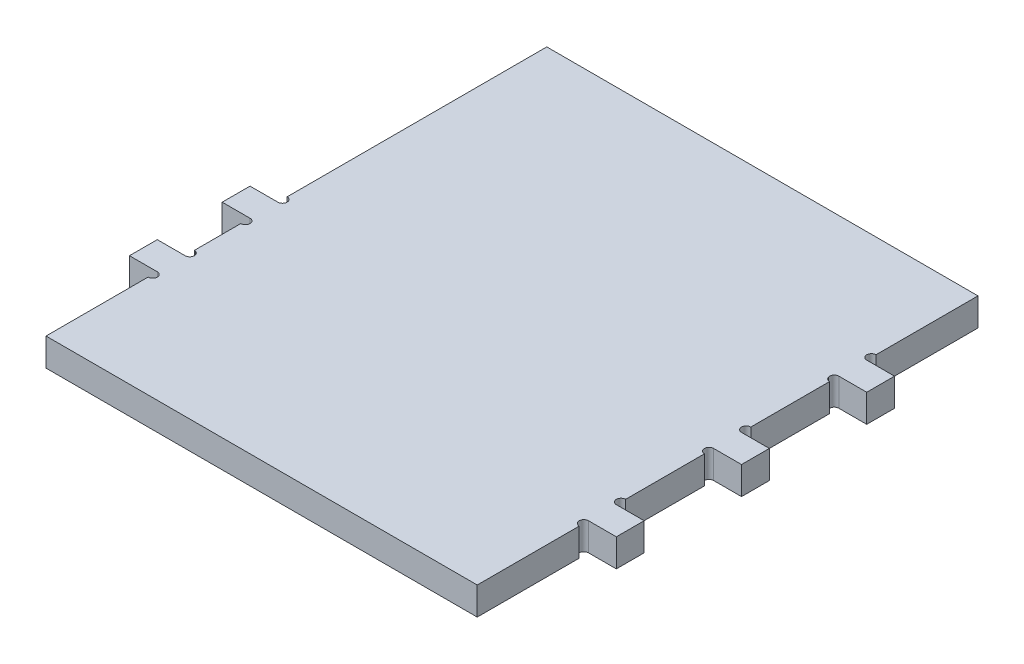
SolidWorks part; units mm, degrees
material "Balsa"
ref_plane "Front Plane" through (0, 0, 0) normal (0, 0, 1) x (1, 0, 0)
ref_plane "Top Plane" through (0, 0, 0) normal (0, 1, 0) x (1, 0, 0)
ref_plane "Right Plane" through (0, 0, 0) normal (1, 0, 0) x (0, 0, -1)
sketch "Sketch1" plane through (0, 0, 0) normal (0, 1, 0) x (1, 0, 0)
  line L1 (0, 0) -> (295.275, 0)
  line L2 (0, 0) -> (0, 76.2)
  line L3 (0, 342.9) -> (295.275, 342.9)
  line L4 (295.275, 0) -> (295.275, 76.2)
  line L5 (0, 76.2) -> (-19.05, 76.2)
  line L7 (0, 95.25) -> (-19.05, 95.25)
  line L8 (-19.05, 76.2) -> (-19.05, 95.25)
  line L9 (0, 139.7) -> (-19.05, 139.7)
  line L11 (0, 158.75) -> (-19.05, 158.75)
  line L12 (-19.05, 139.7) -> (-19.05, 158.75)
  line L13 (295.275, 180.975) -> (314.325, 180.975)
  line L15 (295.275, 161.925) -> (314.325, 161.925)
  line L16 (314.325, 180.975) -> (314.325, 161.925)
  line L17 (295.275, 266.7) -> (314.325, 266.7)
  line L18 (314.325, 266.7) -> (314.325, 247.65)
  line L19 (295.275, 247.65) -> (314.325, 247.65)
  line L20 (295.275, 180.975) -> (295.275, 247.65) construction
  line L22 (295.275, 95.25) -> (314.325, 95.25)
  line L23 (314.325, 95.25) -> (314.325, 76.2)
  line L24 (295.275, 76.2) -> (314.325, 76.2)
  line L25 (295.275, 161.925) -> (295.275, 95.25) construction
  line L26 (0, 158.75) -> (0, 342.9)
  line L27 (0, 95.25) -> (0, 139.7)
  line L29 (295.275, 266.7) -> (295.275, 342.9)
  line L30 (295.275, 180.975) -> (295.275, 247.65)
  line L31 (295.275, 95.25) -> (295.275, 161.925)
  point P17 (314.325, 171.45)
  dimension "D1" = 19.05
  dimension "D2" = 95.25
  dimension "D3" = 342.9
  dimension "D4" = 63.5
  dimension "D5" = 295.275
  dimension "D7" = 85.725
  dimension "D9" = 85.725
  dimension "D10" = 171.45
  dimension "D6" = 2
  dimension "D8" = 2
extrude "Boss-Extrude1" add sketch "Sketch1" along normal blind 19.05
sketch "Sketch2" plane through (0, 19.05, 0) normal (0, 1, 0) x (1, 0, 0)
  line L0 (0, 342.9) -> (0, 158.75) construction
  line L1 (0, 165.1) -> (0, 158.75)
  line L3 (0, 139.7) -> (0, 133.35)
  line L4 (0, 101.6) -> (0, 95.25)
  line L5 (0, 76.2) -> (0, 69.85)
  line L7 (295.275, 266.7) -> (295.275, 342.9) construction
  line L8 (295.275, 273.05) -> (295.275, 266.7)
  line L15 (295.275, 95.25) -> (295.275, 161.925) construction
  line L16 (0, 76.2) -> (0, 0) construction
  line L17 (0, 0) -> (295.275, 0) construction
  line L18 (295.275, 180.975) -> (295.275, 247.65) construction
  line L19 (295.275, 241.3) -> (295.275, 247.65)
  line L20 (295.275, 0) -> (295.275, 76.2) construction
  line L21 (295.275, 101.6) -> (295.275, 95.25)
  line L22 (295.275, 76.2) -> (295.275, 69.85)
  line L23 (295.275, 161.925) -> (295.275, 155.575)
  line L24 (295.275, 187.325) -> (295.275, 180.975)
  arc A0 (0, 158.75) -> (0, 165.1) centre (0, 161.925) ccw
  arc A2 (0, 133.35) -> (0, 139.7) centre (0, 136.525) ccw
  arc A3 (0, 95.25) -> (0, 101.6) centre (0, 98.425) ccw
  arc A4 (0, 69.85) -> (0, 76.2) centre (0, 73.025) ccw
  arc A6 (295.275, 266.7) -> (295.275, 273.05) centre (295.275, 269.875) cw
  arc A12 (295.275, 247.65) -> (295.275, 241.3) centre (295.275, 244.475) ccw
  arc A13 (295.275, 180.975) -> (295.275, 187.325) centre (295.275, 184.15) cw
  arc A14 (295.275, 161.925) -> (295.275, 155.575) centre (295.275, 158.75) ccw
  arc A15 (295.275, 76.2) -> (295.275, 69.85) centre (295.275, 73.025) ccw
  arc A16 (295.275, 95.25) -> (295.275, 101.6) centre (295.275, 98.425) cw
  dimension "D1" = 3.175
extrude "Cut-Extrude1" cut sketch "Sketch2" against normal through all both
